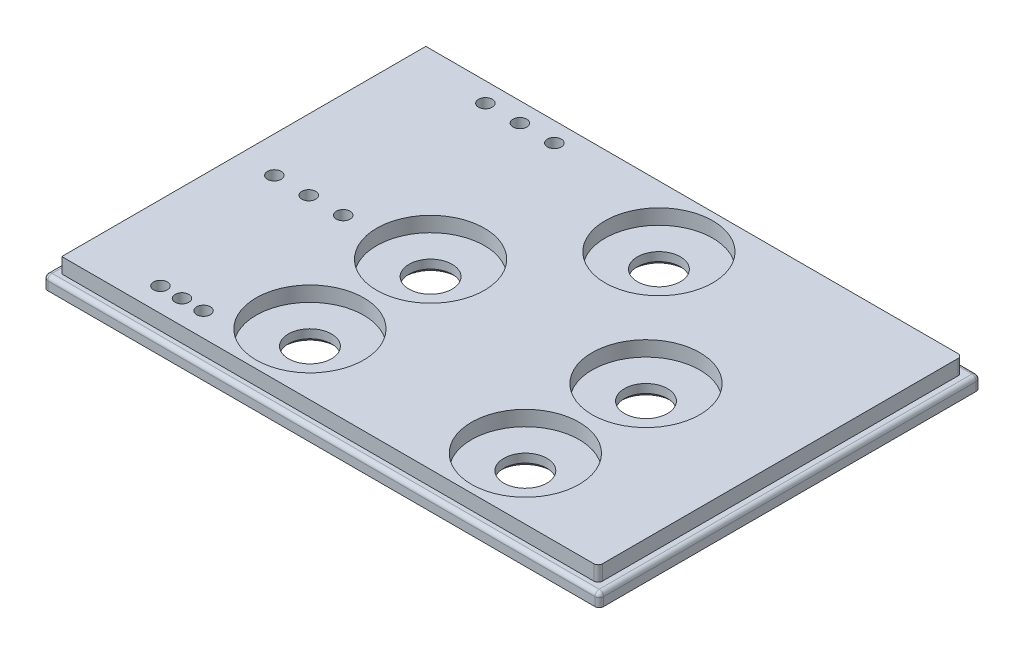
SolidWorks part; units mm, degrees
ref_plane "Спереди" through (0, 0, 0) normal (0, 0, 1) x (1, 0, 0)
ref_plane "Сверху" through (0, 0, 0) normal (0, 1, 0) x (1, 0, 0)
ref_plane "Справа" through (0, 0, 0) normal (1, 0, 0) x (0, 0, -1)
sketch "Эскиз1" plane through (0, 37.5, 0) normal (0, 1, 0) x (1, 0, 0)
  line L1 (127, -2) -> (127, 87) construction
  line L2 (-2, 87) -> (0, 87) construction
  line L3 (127, -2) -> (127, 87) construction
  line L4 (127, -2) -> (0, -2) construction
  line L5 (127, -2) -> (-2, -2) construction
  line L6 (-2, 87) -> (-2, -2) construction
  line L7 (-2, 87) -> (-2, -2) construction
  line L8 (62.5, 87) -> (62.5, -2) construction
  line L9 (-2, 87) -> (0, 87) construction
  line L10 (-2, 86.75) -> (127, 86.75)
  line L11 (-2, 86.75) -> (-2, -1.75)
  line L12 (-2, -1.75) -> (127, -1.75)
  line L13 (127, 86.75) -> (127, -1.75)
  line L14 (-2, 86.75) -> (127, -1.75) construction
  line L15 (-2, -1.75) -> (127, 86.75) construction
  point P8 (62.5, 42.5)
  dimension "D1" = 0.25
  dimension "D2" = 0.25
extrude "Бобышка-Вытянуть1" add sketch "Эскиз1" along normal blind 3
sketch "Эскиз2" plane through (0, 40.5, 0) normal (0, 1, 0) x (1, 0, 0)
  circle A0 centre (43.6, 14.5) radius 5 construction
  circle A1 centre (43.6, 14.5) radius 5 construction
  circle A3 centre (43.6, 42.5) radius 5 construction
  circle A4 centre (68.6, 70.5) radius 5 construction
  circle A5 centre (68.6, 70.5) radius 5 construction
  circle A6 centre (43.6, 42.5) radius 5 construction
  circle A7 centre (93.6, 42.5) radius 5 construction
  circle A8 centre (93.6, 42.5) radius 5 construction
  circle A9 centre (93.6, 14.5) radius 5 construction
  circle A10 centre (93.6, 14.5) radius 5 construction
  circle A11 centre (43.6, 14.5) radius 5
  circle A12 centre (43.6, 42.5) radius 5
  circle A13 centre (68.6, 70.5) radius 5
  circle A14 centre (93.6, 42.5) radius 5
  circle A15 centre (93.6, 14.5) radius 5
  dimension "D1" = 0
extrude "Вырез-Вытянуть1" cut sketch "Эскиз2" against normal through all
sketch "Эскиз3" plane through (0, 40.5, 0) normal (0, 1, 0) x (1, 0, 0)
  circle A0 centre (34.5998, 80.2301) radius 1.6
  circle A1 centre (27.5999, 5.8) radius 1.5
  circle A2 centre (27.5999, 5.8) radius 1.5 construction
  circle A3 centre (22.5999, 5.8) radius 1.5
  circle A4 centre (22.5999, 5.8) radius 1.5 construction
  circle A5 centre (17.5999, 5.8) radius 1.5
  circle A6 centre (17.5999, 5.8) radius 1.5 construction
  circle A7 centre (34.5998, 80.2301) radius 1.5
  circle A8 centre (34.5998, 80.2301) radius 1.5 construction
  circle A9 centre (26.6, 80.2299) radius 1.5
  circle A10 centre (26.6, 80.2299) radius 1.5 construction
  circle A11 centre (18.5998, 80.2301) radius 1.5
  circle A12 centre (18.5998, 80.2301) radius 1.5 construction
  circle A13 centre (8.5998, 41.2301) radius 1.5
  circle A14 centre (8.5998, 41.2301) radius 1.5 construction
  circle A15 centre (16.5998, 41.2301) radius 1.5
  circle A16 centre (16.5998, 41.2301) radius 1.5 construction
  circle A17 centre (24.6, 41.2299) radius 1.5
  circle A18 centre (24.6, 41.2299) radius 1.5 construction
  circle A19 centre (26.6, 80.2299) radius 1.6
  circle A20 centre (18.5998, 80.2301) radius 1.6
  circle A21 centre (8.5998, 41.2301) radius 1.6
  circle A22 centre (16.5998, 41.2301) radius 1.6
  circle A23 centre (24.6, 41.2299) radius 1.6
  circle A24 centre (17.5999, 5.8) radius 1.6
  circle A25 centre (22.5999, 5.8) radius 1.6
  circle A26 centre (27.5999, 5.8) radius 1.6
  dimension "D10" = 3.2
  dimension "D1" = 0
  dimension "D2" = 0
  dimension "D3" = 0
  dimension "D4" = 0
  dimension "D5" = 0
  dimension "D6" = 0
  dimension "D7" = 0
  dimension "D8" = 0
  dimension "D9" = 0
extrude "Вырез-Вытянуть2" cut sketch "Эскиз3" against normal through all
sketch "Эскиз4" plane through (0, 37.5, 0) normal (0, -1, 0) x (1, 0, 0)
  line L0 (17.5999, -5.8) -> (27.5999, -5.8) construction
  line L1 (17.5999, -2.2) -> (27.5999, -2.2)
  line L2 (17.5999, -9.4) -> (27.5999, -9.4)
  circle A0 centre (27.5999, -5.8) radius 1.6 construction
  circle A1 centre (22.5999, -5.8) radius 1.6 construction
  circle A2 centre (17.5999, -5.8) radius 1.6 construction
  circle A3 centre (27.5999, -5.8) radius 1.6
  circle A4 centre (22.5999, -5.8) radius 1.6
  circle A5 centre (17.5999, -5.8) radius 1.6
  arc A6 (17.5999, -2.2) -> (17.5999, -9.4) centre (17.5999, -5.8) ccw
  arc A7 (27.5999, -9.4) -> (27.5999, -2.2) centre (27.5999, -5.8) ccw
  point P9 (22.5999, -5.8)
  dimension "D1" = 2
chamfer "Фаска1" distance 1 angle 45 5 edges at (93.6, 37.5, -9.5) (93.6, 37.5, -37.5) (68.6, 37.5, -65.5) (43.6, 37.5, -37.5) (43.6, 37.5, -9.5)
chamfer "Фаска2" distance 1 angle 45 6 edges at (34.5998, 37.5, -78.6301) (26.6, 37.5, -78.6299) (18.5998, 37.5, -78.6301) (24.6, 37.5, -39.6299) (16.5998, 37.5, -39.6301) (8.5998, 37.5, -39.6301)
sketch "Эскиз6" plane through (0, 40.5, 0) normal (0, 1, 0) x (1, 0, 0)
  line L0 (125, 0) -> (0, 0) construction
  line L1 (125, 0) -> (125, 85) construction
  line L2 (125, 0) -> (0, 0) construction
  line L3 (125, 0) -> (125, 85) construction
  line L4 (0, -4) -> (0, 89) construction
  line L5 (0, -4) -> (0, 89) construction
  line L6 (125, 85) -> (0, 85) construction
  line L7 (125, 85) -> (0, 85) construction
  line L8 (62.5, 85) -> (62.5, 0) construction
  line L10 (124.75, 0.25) -> (0.25, 0.25)
  line L11 (124.75, 0.25) -> (124.75, 84.75)
  line L12 (124.75, 84.75) -> (0.25, 84.75)
  line L13 (0.25, 0.25) -> (0.25, 84.75)
  line L14 (124.75, 0.25) -> (0.25, 84.75) construction
  line L15 (124.75, 84.75) -> (0.25, 0.25) construction
  point P8 (62.5, 42.5)
  dimension "D1" = 0.25
  dimension "D2" = 0.25
extrude "Бобышка-Вытянуть3" add sketch "Эскиз6" along normal blind 3.5
sketch "Эскиз7" plane through (0, 40.5, 0) normal (0, -1, 0) x (1, 0, 0)
  circle A0 centre (26.6, -80.2299) radius 1.6 construction
  circle A1 centre (43.6, -42.5) radius 5
  circle A2 centre (43.6, -42.5) radius 5
  circle A3 centre (43.6, -14.5) radius 5
  circle A4 centre (43.6, -14.5) radius 5
  circle A5 centre (93.6, -14.5) radius 5
  circle A6 centre (93.6, -14.5) radius 5
  circle A7 centre (93.6, -42.5) radius 5
  circle A8 centre (93.6, -42.5) radius 5
  circle A9 centre (68.6, -70.5) radius 5
  circle A10 centre (68.6, -70.5) radius 5
  circle A11 centre (24.6, -41.2299) radius 1.6
  circle A12 centre (24.6, -41.2299) radius 1.6
  circle A13 centre (16.5998, -41.2301) radius 1.6
  circle A14 centre (16.5998, -41.2301) radius 1.6
  circle A15 centre (8.5998, -41.2301) radius 1.6
  circle A16 centre (8.5998, -41.2301) radius 1.6
  circle A17 centre (18.5998, -80.2301) radius 1.6
  circle A18 centre (18.5998, -80.2301) radius 1.6
  circle A19 centre (26.6, -80.2299) radius 1.6
  circle A21 centre (34.5998, -80.2301) radius 1.6
  circle A22 centre (34.5998, -80.2301) radius 1.6
  circle A23 centre (17.5999, -5.8) radius 1.6
  circle A24 centre (17.5999, -5.8) radius 1.6
  circle A25 centre (22.5999, -5.8) radius 1.6
  circle A26 centre (22.5999, -5.8) radius 1.6
  circle A27 centre (27.5999, -5.8) radius 1.6
  circle A28 centre (27.5999, -5.8) radius 1.6
  dimension "D1" = 0
  dimension "D2" = 0
  dimension "D3" = 0
  dimension "D4" = 0
  dimension "D5" = 0
  dimension "D6" = 0
  dimension "D7" = 0
  dimension "D8" = 0
  dimension "D9" = 0
  dimension "D10" = 0
  dimension "D11" = 0
  dimension "D12" = 0
  dimension "D13" = 0
extrude "Вырез-Вытянуть3" cut sketch "Эскиз7" against normal through all
sketch "Эскиз8" plane through (0, 44, 0) normal (0, 1, 0) x (1, 0, 0)
  line L0 (17.5999, 2.2) -> (27.5999, 2.2) construction
  line L1 (17.5999, 2.2) -> (27.5999, 2.2)
  line L2 (17.5999, 9.4) -> (27.5999, 9.4) construction
  line L3 (17.5999, 9.4) -> (27.5999, 9.4)
  arc A0 (17.5999, 9.4) -> (17.5999, 2.2) centre (17.5999, 5.8) ccw construction
  arc A1 (17.5999, 9.4) -> (17.5999, 2.2) centre (17.5999, 5.8) ccw
  arc A2 (27.5999, 2.2) -> (27.5999, 9.4) centre (27.5999, 5.8) ccw construction
  arc A3 (27.5999, 2.2) -> (27.5999, 9.4) centre (27.5999, 5.8) ccw
  circle A4 centre (17.5999, 5.8) radius 1.6 construction
  circle A5 centre (22.5999, 5.8) radius 1.6 construction
  circle A6 centre (27.5999, 5.8) radius 1.6 construction
  circle A7 centre (17.5999, 5.8) radius 1.6
  circle A8 centre (22.5999, 5.8) radius 1.6
  circle A9 centre (27.5999, 5.8) radius 1.6
sketch "Эскиз9" plane through (0, 44, 0) normal (0, 1, 0) x (1, 0, 0)
  circle A0 centre (43.6, 14.5) radius 12.5
  circle A1 centre (43.6, 42.5) radius 12.5
  circle A2 centre (68.6, 70.5) radius 12.5
  circle A3 centre (93.6, 42.5) radius 12.5
  circle A4 centre (93.6, 14.5) radius 12.5
  dimension "D1" = 25
extrude "Вырез-Вытянуть4" cut sketch "Эскиз9" against normal blind 3.5
fillet "Скругление4" radius 1 4 edges at (127, 39, 1.75) (124.75, 42.25, -0.25) (124.75, 42.25, -84.75) (127, 39, -86.75)
fillet "Скругление5" radius 1 5 edges at (62, 40.5, 1.75) (126.7071, 40.5, 1.4571) (127, 40.5, -42.5) (126.7071, 40.5, -86.4571) (62, 40.5, -86.75)
fillet "Скругление6" radius 1 5 edges at (-2, 38.5, 1.75) (-2, 40.2071, 1.4571) (-2, 40.5, -42.5) (-2, 40.2071, -86.4571) (-2, 38.5, -86.75)
